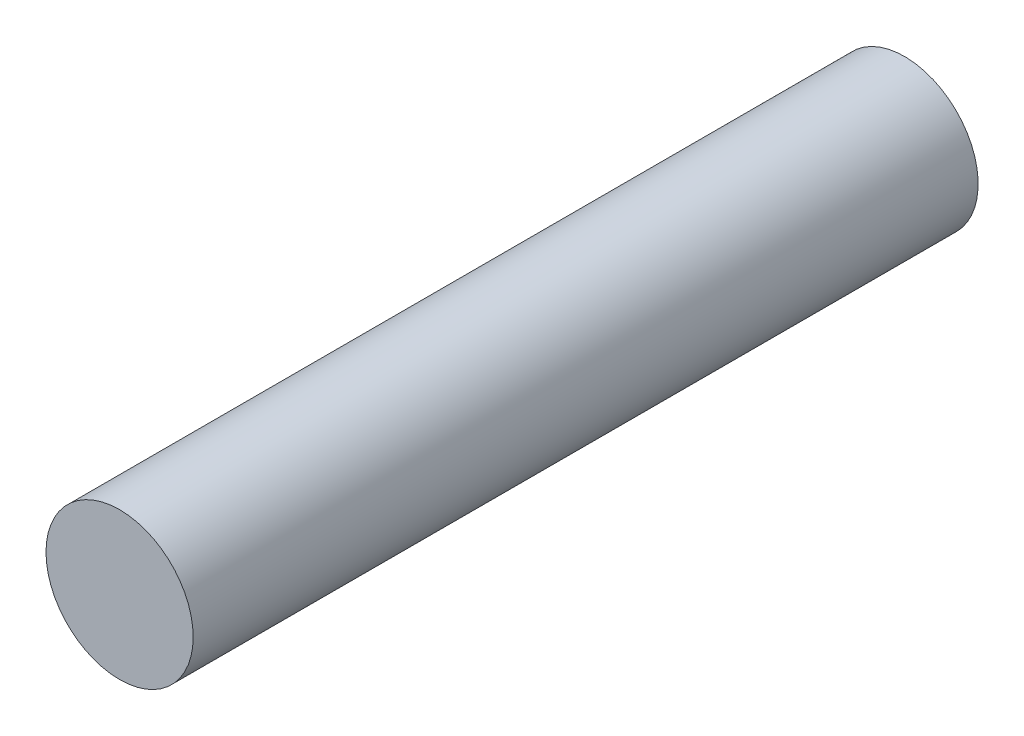
SolidWorks part; units mm, degrees
material "Alliage 1060"
ref_plane "Plan de face" through (0, 0, 0) normal (0, 0, 1) x (1, 0, 0)
ref_plane "Plan de dessus" through (0, 0, 0) normal (0, 1, 0) x (1, 0, 0)
ref_plane "Plan de droite" through (0, 0, 0) normal (1, 0, 0) x (0, 0, -1)
sketch "Esquisse1" plane through (0, 0, 0) normal (0, 0, 1) x (1, 0, 0)
  circle A0 centre (0, 0) radius 3
  dimension "D1" = 6
extrude "Boss.-Extru.1" add sketch "Esquisse1" along normal blind 53.5
sketch "Esquisse2" [suppressed] plane through (0, 0, 150) normal (0, 0, 1) x (1, 0, 0)
  circle A1 centre (0, 0) radius 3
  circle A2 centre (0, 0) radius 3
  dimension "D1" = 0
extrude "Enlèv. mat.-Extru.1" [suppressed] cut sketch "Esquisse2" against normal blind 60
sketch "Esquisse3" plane through (0, 0, 53.5) normal (0, 0, 1) x (1, 0, 0)
  circle A1 centre (0, 0) radius 3
  circle A2 centre (0, 0) radius 3
  dimension "D1" = 0
extrude "Enlèv. mat.-Extru.2" [suppressed] cut sketch "Esquisse3" against normal blind 29.6
sketch "Esquisse4" [suppressed] plane through (0, 0, 0) normal (0, 0, -1) x (-1, 0, 0)
  circle A1 centre (0, 0) radius 3
  circle A2 centre (0, 0) radius 3
  dimension "D1" = 0
extrude "Enlèv. mat.-Extru.3" [suppressed] cut sketch "Esquisse4" against normal blind 15.1
sketch "Esquisse5" plane through (0, 0, 0) normal (0, 0, -1) x (-1, 0, 0)
  circle A1 centre (0, 0) radius 3
  circle A2 centre (0, 0) radius 3
  dimension "D1" = 0
extrude "Enlèv. mat.-Extru.4" cut sketch "Esquisse5" against normal blind 21.5
